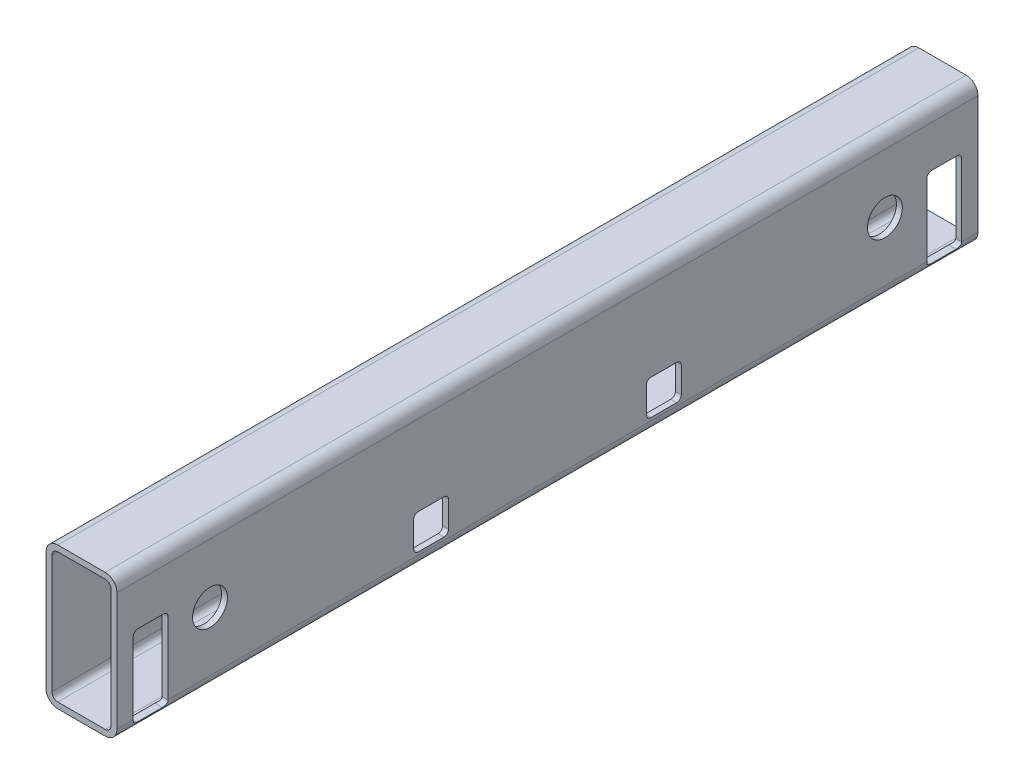
SolidWorks part; units mm, degrees
material "Low Carbon Steel"
ref_plane "Front Plane" through (0, 0, 0) normal (0, 0, 1) x (1, 0, 0)
ref_plane "Top Plane" through (0, 0, 0) normal (0, 1, 0) x (1, 0, 0)
ref_plane "Right Plane" through (0, 0, 0) normal (1, 0, 0) x (0, 0, -1)
sketch "Sketch1" plane through (0, 0, 0) normal (0, 0, 1) x (1, 0, 0)
  line L0 (-50.8, -139.7) -> (50.8, -139.7)
  line L1 (-63.5, -127) -> (-63.5, 127)
  line L2 (50.8, 139.7) -> (-50.8, 139.7)
  line L3 (63.5, 127) -> (63.5, -127)
  line L4 (-50.8, -152.4) -> (50.8, -152.4)
  line L5 (-76.2, -127) -> (-76.2, 127)
  line L6 (50.8, 152.4) -> (-50.8, 152.4)
  line L7 (76.2, 127) -> (76.2, -127)
  line L8 (-50.8, -127) -> (50.8, 127) construction
  arc A0 (76.2, 127) -> (50.8, 152.4) centre (50.8, 127) ccw
  arc A1 (50.8, -152.4) -> (76.2, -127) centre (50.8, -127) ccw
  arc A2 (-76.2, -127) -> (-50.8, -152.4) centre (-50.8, -127) ccw
  arc A3 (-50.8, 152.4) -> (-76.2, 127) centre (-50.8, 127) ccw
  arc A4 (-50.8, 139.7) -> (-63.5, 127) centre (-50.8, 127) ccw
  arc A5 (63.5, 127) -> (50.8, 139.7) centre (50.8, 127) ccw
  arc A6 (50.8, -139.7) -> (63.5, -127) centre (50.8, -127) ccw
  arc A7 (-63.5, -127) -> (-50.8, -139.7) centre (-50.8, -127) ccw
extrude "Boss-Extrude1" add sketch "Sketch1" along normal mid plane 1850
sketch "Sketch2" plane through (76.2, 0, 0) normal (1, 0, 0) x (0, 0, -1)
  line L0 (-925, -127) -> (-925, 127) construction
  line L1 (-880, 37.6) -> (-825, 37.6)
  line L2 (-890, 27.6) -> (-890, -127.4)
  line L3 (-880, -137.4) -> (-825, -137.4)
  line L4 (-815, 27.6) -> (-815, -127.4)
  line L5 (825, 37.6) -> (880, 37.6)
  line L6 (815, 27.6) -> (815, -127.4)
  line L7 (825, -137.4) -> (880, -137.4)
  line L8 (890, 27.6) -> (890, -127.4)
  line L9 (-925, -152.4) -> (925, -152.4) construction
  line L10 (925, -127) -> (925, 127) construction
  arc A0 (-825, 37.6) -> (-815, 27.6) centre (-825, 27.6) cw
  arc A1 (-890, -127.4) -> (-880, -137.4) centre (-880, -127.4) ccw
  arc A2 (-825, -137.4) -> (-815, -127.4) centre (-825, -127.4) ccw
  arc A3 (-880, 37.6) -> (-890, 27.6) centre (-880, 27.6) ccw
  arc A4 (880, 37.6) -> (890, 27.6) centre (880, 27.6) cw
  arc A5 (815, -127.4) -> (825, -137.4) centre (825, -127.4) ccw
  arc A6 (880, -137.4) -> (890, -127.4) centre (880, -127.4) ccw
  arc A7 (825, 37.6) -> (815, 27.6) centre (825, 27.6) ccw
  dimension "D5" = 10
  dimension "D6" = 10
  dimension "D1" = 35
  dimension "D2" = 75
  dimension "D3" = 175
  dimension "D4" = 15
  dimension "D7" = 35
extrude "Cut-Extrude1" cut sketch "Sketch2" against normal blind 30
sketch "Sketch3" plane through (76.2, 0, 0) normal (1, 0, 0) x (0, 0, -1)
  line L0 (-925, -152.4) -> (925, -152.4) construction
  line L1 (-277.5, -45.65) -> (-222.5, -45.65)
  line L2 (-287.5, -55.65) -> (-287.5, -110.65)
  line L3 (-277.5, -120.65) -> (-222.5, -120.65)
  line L4 (-212.5, -55.65) -> (-212.5, -110.65)
  line L5 (222.5, -45.65) -> (277.5, -45.65)
  line L6 (212.5, -55.65) -> (212.5, -110.65)
  line L7 (222.5, -120.65) -> (277.5, -120.65)
  line L8 (287.5, -55.65) -> (287.5, -110.65)
  line L9 (-212.5, -45.65) -> (212.5, -45.65) construction
  line L10 (0, -45.65) -> (0, 0) construction
  arc A0 (-287.5, -110.65) -> (-277.5, -120.65) centre (-277.5, -110.65) ccw
  arc A1 (-222.5, -120.65) -> (-212.5, -110.65) centre (-222.5, -110.65) ccw
  arc A2 (-277.5, -45.65) -> (-287.5, -55.65) centre (-277.5, -55.65) ccw
  arc A3 (-222.5, -45.65) -> (-212.5, -55.65) centre (-222.5, -55.65) cw
  arc A4 (212.5, -110.65) -> (222.5, -120.65) centre (222.5, -110.65) ccw
  arc A5 (222.5, -45.65) -> (212.5, -55.65) centre (222.5, -55.65) ccw
  arc A6 (277.5, -45.65) -> (287.5, -55.65) centre (277.5, -55.65) cw
  arc A7 (277.5, -120.65) -> (287.5, -110.65) centre (277.5, -110.65) ccw
  dimension "D5" = 10
  dimension "D1" = 75
  dimension "D2" = 75
  dimension "D3" = 31.75
  dimension "D4" = 500
extrude "for mach shop confirm w/ programming" cut sketch "Sketch3" against normal up to next
sketch "Sketch5" plane through (-76.2, 0, 0) normal (-1, 0, 0) x (0, 0, 1)
  line L0 (725, 0) -> (-725, 0) construction
  line L1 (925, 127) -> (925, -127) construction
  circle A0 centre (725, 0) radius 37.5
  circle A1 centre (-725, 0) radius 37.5
  dimension "D1" = 75
  dimension "D2" = 200
extrude "Cut-Extrude3" cut sketch "Sketch5" against normal through all
other "Freeze***"
